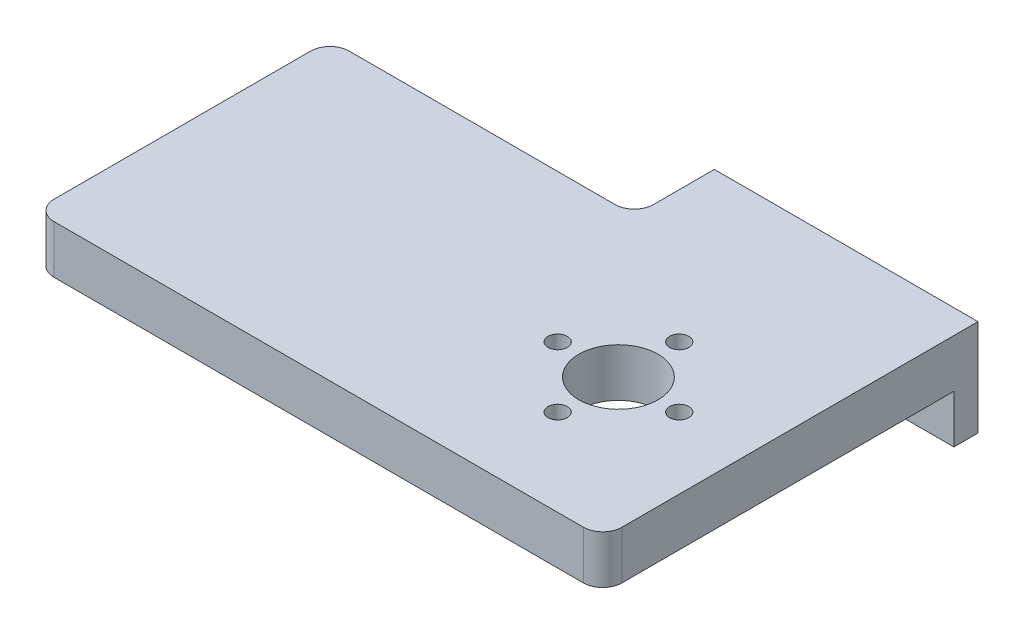
SolidWorks part; units mm, degrees
material "ABS"
ref_plane "Front Plane" through (0, 0, 0) normal (0, 0, 1) x (1, 0, 0)
ref_plane "Top Plane" through (0, 0, 0) normal (0, 1, 0) x (1, 0, 0)
ref_plane "Right Plane" through (0, 0, 0) normal (1, 0, 0) x (0, 0, -1)
sketch "Sketch1" plane through (0, 0, 0) normal (0, 1, 0) x (1, 0, 0)
  line L0 (-35.9136, -11.9609) -> (-2.2932, -11.9609) construction
  line L1 (-2.2096, 1.7551) -> (-2.2096, -8.7859)
  line L2 (-42.2636, -8.7859) -> (32.4904, -8.7859)
  line L3 (-42.2636, -8.7859) -> (-42.2636, -47.6479)
  line L4 (-42.2636, -47.6479) -> (32.4904, -47.6479)
  line L5 (32.4904, -8.7859) -> (32.4904, -47.6479)
  line L6 (32.4904, 1.7551) -> (-2.2096, 1.7551)
  line L7 (-35.9136, -44.4729) -> (-2.2932, -44.4729) construction
  line L8 (-35.9136, -8.7859) -> (-35.9136, -47.6479) construction
  line L9 (32.4904, 1.7551) -> (32.4904, -8.7859)
  line L10 (26.1404, -8.7859) -> (26.1404, -47.6479) construction
  line L11 (4.1404, -8.7859) -> (4.1404, -47.6479) construction
  circle A0 centre (-19.6576, -28.2169) radius 16.256
  circle A1 centre (15.1404, -28.2169) radius 5.207
  circle A2 centre (15.1404, -28.2169) radius 11 construction
  dimension "D2" = 32.512
  dimension "D3" = 10.414
  dimension "D4" = 22
  dimension "D1" = 29.972
  dimension "D5" = 3.175
  dimension "D6" = 3.175
  dimension "D7" = 34.798
  dimension "D8" = 6.35
  dimension "D9" = 6.35
  dimension "D10" = 6.35
extrude "Boss-Extrude1" add sketch "Sketch1" along normal blind 6.35 contours L5 L2 L3 L4 A1 A0 | L9 L6 L1 L2
sketch "Sketch2" plane through (0, 6.35, 0) normal (0, 1, 0) x (1, 0, 0)
  circle A0 centre (-19.6576, -28.2169) radius 16.256 construction
  circle A1 centre (-19.6576, -28.2169) radius 16.256
extrude "Boss-Extrude2" add sketch "Sketch2" against normal blind 3.175
sketch "Sketch3" plane through (0, 6.35, 0) normal (0, 1, 0) x (1, 0, 0)
  line L0 (32.4904, 1.7551) -> (32.4904, -47.6479) construction
  line L1 (-2.2096, 1.7551) -> (32.4904, 1.7551)
  line L2 (-2.2096, 1.7551) -> (-2.2096, -1.4199)
  line L3 (-2.2096, -1.4199) -> (32.4904, -1.4199)
  line L4 (32.4904, 1.7551) -> (32.4904, -1.4199)
  dimension "D1" = 3.175
extrude "Boss-Extrude3" add sketch "Sketch3" against normal blind 12.7
fillet "Fillet1" radius 2.54 4 edges at (-2.2096, 3.175, 8.7859) (-42.2636, 3.175, 8.7859) (-42.2636, 3.175, 47.6479) (32.4904, 3.175, 47.6479)
sketch "Sketch4" plane through (0, 6.35, 0) normal (0, 1, 0) x (1, 0, 0)
  circle A0 centre (15.1404, -28.2169) radius 8.001 construction
  circle A1 centre (15.1404, -20.2159) radius 1.27
  circle A2 centre (23.1414, -28.2169) radius 1.27
  circle A3 centre (15.1404, -36.2179) radius 1.27
  circle A4 centre (7.1394, -28.2169) radius 1.27
  dimension "D1" = 16.002
  dimension "D2" = 2.54
  dimension "D3" = 2.54
  dimension "D4" = 2.54
  dimension "D5" = 2.54
extrude "Cut-Extrude1" cut sketch "Sketch4" against normal through all
